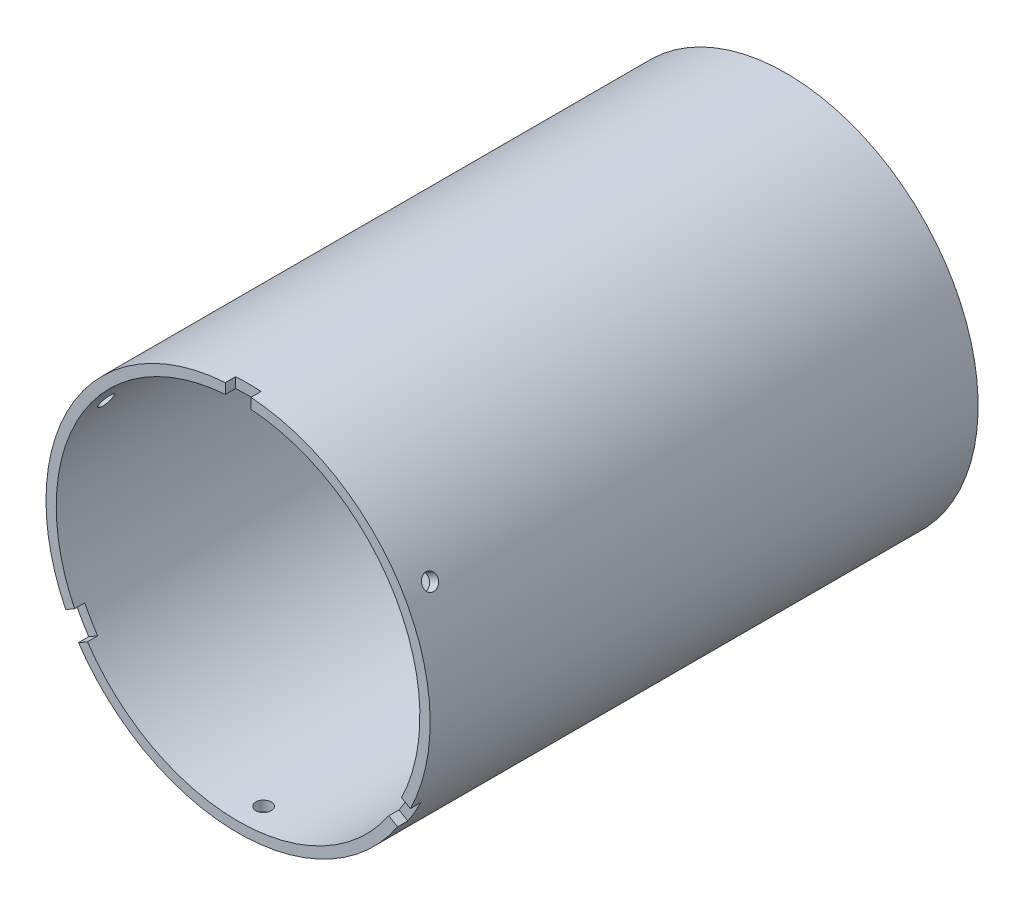
SolidWorks part; units mm, degrees
material "1060 Сплав"
ref_plane "Спереди" through (0, 0, 0) normal (0, 0, 1) x (1, 0, 0)
ref_plane "Сверху" through (0, 0, 0) normal (0, 1, 0) x (1, 0, 0)
ref_plane "Справа" through (0, 0, 0) normal (1, 0, 0) x (0, 0, -1)
sketch "Эскиз1" plane through (0, 0, 0) normal (0, 0, 1) x (1, 0, 0)
  circle A0 centre (0, 0) radius 37.5
  circle A1 centre (0, 0) radius 35.5
  dimension "D1" = 75
  dimension "D2" = 2
extrude "Бобышка-Вытянуть1" add sketch "Эскиз1" along normal blind 214
sketch "Эскиз2" plane through (0, 0, 0) normal (0, 1, 0) x (1, 0, 0)
  line L0 (0, 0) -> (0, -214) construction
  line L1 (35.5, 0) -> (-35.5, 0) construction
  line L2 (-37.5, -214) -> (37.5, -214) construction
  line L3 (37.5, 0) -> (-37.5, 0) construction
  circle A0 centre (0, -5) radius 1.5
  circle A1 centre (0, -209) radius 1.5
  dimension "D1" = 3
  dimension "D4" = 3
  dimension "D2" = 5
  dimension "D3" = 5
extrude "Вырез-Вытянуть1" cut sketch "Эскиз2" against normal blind 88
pattern_circular "Круговой массив1" count 3 over 360 about axis through (0, 0, 214) along (0, 0, -1) of "Вырез-Вытянуть1"
sketch "Эскиз3" plane through (0, 0, 0) normal (0, 0, -1) x (-1, 0, 0)
  line L0 (0, 0) -> (0, 38.5898) construction
  line L2 (-2.5, 37.5092) -> (2.5, 37.5092)
  line L3 (-2.5, 37.5092) -> (-2.5, 17.134)
  line L4 (-2.5, 17.134) -> (2.5, 17.134)
  line L5 (2.5, 37.5092) -> (2.5, 17.134)
  line L6 (-2.5, 37.5092) -> (2.5, 17.134) construction
  line L7 (-2.5, 17.134) -> (2.5, 37.5092) construction
  point P4 (0, 27.3216)
  dimension "D1" = 5
extrude "Вырез-Вытянуть2" cut sketch "Эскиз3" against normal blind 2
pattern_circular "Круговой массив2" count 3 over 360 about axis through (0, 0, 0) along (0, 0, 1) of "Вырез-Вытянуть2"
sketch "Эскиз4" plane through (0, 0, 214) normal (0, 0, 1) x (1, 0, 0)
  line L4 (2.5, 37.5092) -> (-2.5, 37.5092)
  line L5 (-2.5, 37.5092) -> (-2.5, 17.134)
  line L6 (-2.5, 17.134) -> (2.5, 17.134)
  line L7 (2.5, 17.134) -> (2.5, 37.5092)
  line L8 (2.5, 37.5092) -> (-2.5, 37.5092)
  line L9 (-2.5, 37.5092) -> (-2.5, 17.134)
  line L10 (-2.5, 17.134) -> (2.5, 17.134)
  line L11 (2.5, 17.134) -> (2.5, 37.5092)
  dimension "D1" = 0
extrude "Вырез-Вытянуть3" cut sketch "Эскиз4" against normal blind 2
pattern_circular "Круговой массив3" count 3 over 360 about axis through (0, 0, 0) along (0, 0, 1) of "Вырез-Вытянуть3"
sketch "Эскиз5" plane through (0, 0, 0) normal (0, 1, 0) x (1, 0, 0)
  line L0 (37.5, 0) -> (2.5, 0) construction
  line L1 (-82.3814, 107) -> (82.3814, 107)
  line L2 (-82.3814, 107) -> (-82.3814, -107)
  line L3 (-82.3814, -107) -> (82.3814, -107)
  line L4 (82.3814, 107) -> (82.3814, -107)
  line L5 (-82.3814, 107) -> (82.3814, -107) construction
  line L6 (-82.3814, -107) -> (82.3814, 107) construction
  point P0 (0, 0)
  dimension "D1" = 107
extrude "Вырез-Вытянуть4" cut sketch "Эскиз5" against normal blind 165 and the other way blind 156
